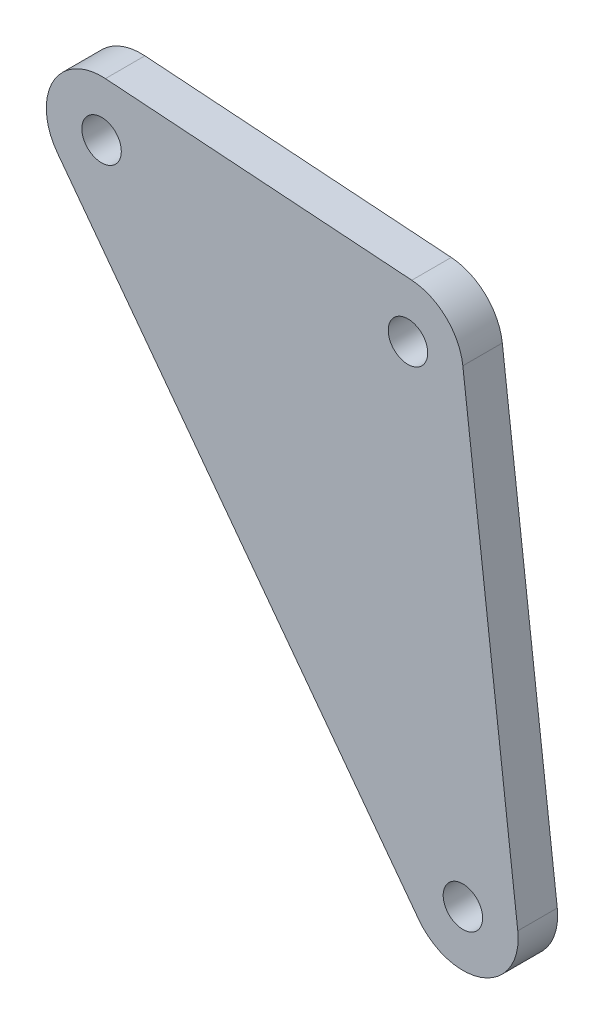
SolidWorks part; units mm, degrees
ref_plane "Front Plane" through (0, 0, 0) normal (0, 0, 1) x (1, 0, 0)
ref_plane "Top Plane" through (0, 0, 0) normal (0, 1, 0) x (1, 0, 0)
ref_plane "Right Plane" through (0, 0, 0) normal (1, 0, 0) x (0, 0, -1)
sketch "Sketch1" plane through (0, 0, 0) normal (0, 0, 1) x (1, 0, 0)
  line L0 (-7.8295, -30.9143) -> (41.4564, -34.3577) construction
  line L1 (41.4564, -34.3577) -> (50.2975, -108.6515) construction
  line L2 (50.2975, -108.6515) -> (-7.8295, -30.9143) construction
  line L3 (-26.5727, -20.6932) -> (49.4148, -26.002)
  line L4 (49.4148, -26.002) -> (63.0457, -140.546)
  line L5 (63.0457, -140.546) -> (-26.5727, -20.6932)
  circle A0 centre (-7.8295, -30.9143) radius 3.175
  circle A1 centre (41.4564, -34.3577) radius 3.175
  circle A2 centre (50.2975, -108.6515) radius 3.175
  dimension "D4" = 6.35
  dimension "D1" = 49.406
  dimension "D2" = 74.818
  dimension "D3" = 97.066
  dimension "D5" = 8.89
extrude "Boss-Extrude1" add sketch "Sketch1" along normal blind 6.35
fillet "Fillet1" radius 8.89 3 edges at (63.0457, -140.546, 3.175) (-26.5727, -20.6932, 3.175) (49.4148, -26.002, 3.175)
